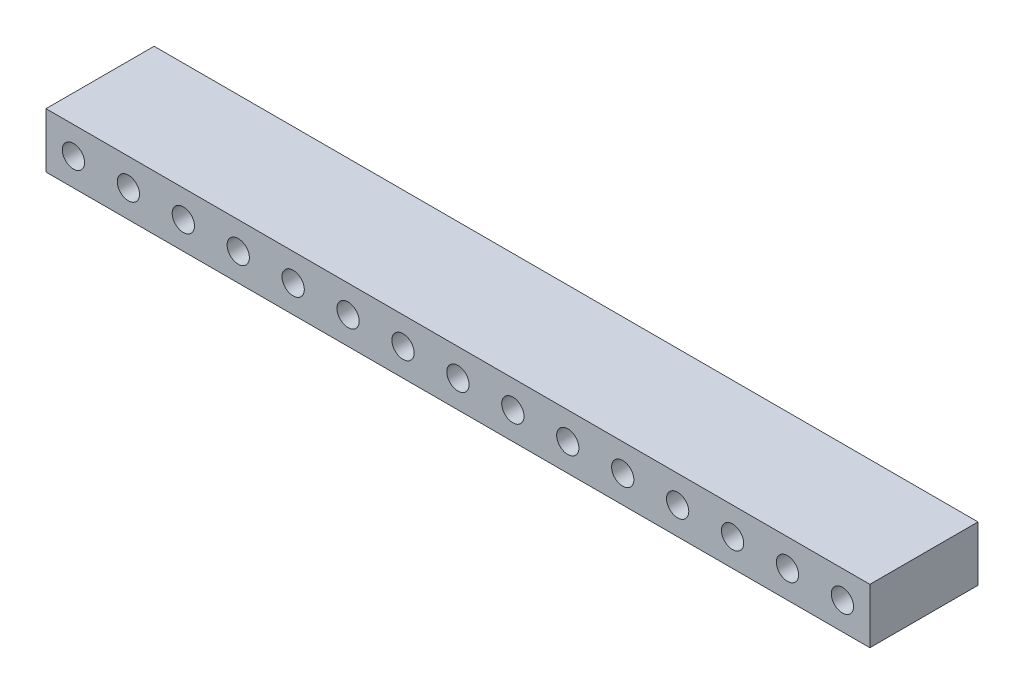
SolidWorks part; units mm, degrees
ref_plane "Front Plane" through (0, 0, 0) normal (0, 0, 1) x (1, 0, 0)
ref_plane "Top Plane" through (0, 0, 0) normal (0, 1, 0) x (1, 0, 0)
ref_plane "Right Plane" through (0, 0, 0) normal (1, 0, 0) x (0, 0, -1)
sketch "Sketch1" plane through (0, 0, 0) normal (0, 0, 1) x (1, 0, 0)
  line L1 (0, 0) -> (38.1, 0)
  line L2 (0, 0) -> (0, 2.54)
  line L3 (0, 2.54) -> (38.1, 2.54)
  line L4 (38.1, 0) -> (38.1, 2.54)
  dimension "D1" = 2.54
  dimension "D2" = 38.1
extrude "Boss-Extrude1" add sketch "Sketch1" along normal blind 5
sketch "Sketch2" plane through (0, 0, 5) normal (0, 0, 1) x (1, 0, 0)
  line L0 (0, 2.54) -> (0, 0) construction
  line L1 (38.1, 2.54) -> (0, 2.54) construction
  circle A0 centre (1.27, 1.27) radius 0.5151
  circle A1 centre (3.81, 1.27) radius 0.5151
  circle A2 centre (6.35, 1.27) radius 0.5151
  circle A3 centre (8.89, 1.27) radius 0.5151
  circle A4 centre (11.43, 1.27) radius 0.5151
  circle A5 centre (13.97, 1.27) radius 0.5151
  circle A6 centre (16.51, 1.27) radius 0.5151
  circle A7 centre (19.05, 1.27) radius 0.5151
  circle A8 centre (21.59, 1.27) radius 0.5151
  circle A9 centre (24.13, 1.27) radius 0.5151
  circle A10 centre (26.67, 1.27) radius 0.5151
  circle A11 centre (29.21, 1.27) radius 0.5151
  circle A12 centre (31.75, 1.27) radius 0.5151
  circle A13 centre (34.29, 1.27) radius 0.5151
  circle A14 centre (36.83, 1.27) radius 0.5151
  dimension "D1" = 1.27
  dimension "D2" = 1.27
  dimension "D3" = 15
extrude "Cut-Extrude1" cut sketch "Sketch2" against normal through all
